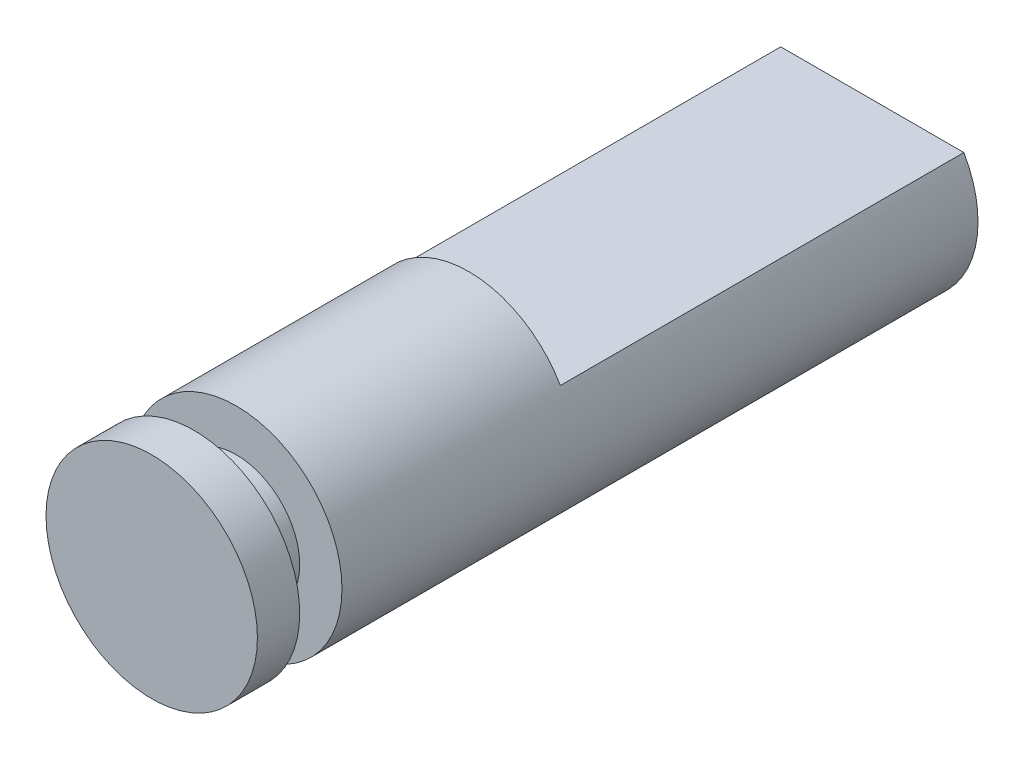
SolidWorks part; units mm, degrees
ref_plane "Front Plane" through (0, 0, 0) normal (0, 0, 1) x (1, 0, 0)
ref_plane "Top Plane" through (0, 0, 0) normal (0, 1, 0) x (1, 0, 0)
ref_plane "Right Plane" through (0, 0, 0) normal (1, 0, 0) x (0, 0, -1)
sketch "Sketch1" plane through (0, 0, 0) normal (0, 0, 1) x (1, 0, 0)
  line L1 (0, 2.5) -> (-4.3301, 2.5)
  line L2 (0, 2.5) -> (4.3301, 2.5)
  arc A0 (-4.3301, 2.5) -> (4.3301, 2.5) centre (0, 0) ccw
  dimension "D1" = 10
extrude "Boss-Extrude1" add sketch "Sketch1" along normal blind 19.0848
sketch "Sketch2" plane through (0, 0, 19.0848) normal (0, 0, 1) x (1, 0, 0)
  circle A0 centre (0, 0) radius 5
extrude "Boss-Extrude2" add sketch "Sketch2" along normal blind 15
ref_plane "Plane1" through (0, 0, 32.0848) normal (0, 0, 1) x (1, 0, 0)
sketch "Sketch3" plane through (0, 0, 32.0848) normal (0, 0, 1) x (1, 0, 0)
  circle A0 centre (0, 0) radius 3
  circle A1 centre (0, 0) radius 5
  circle A2 centre (0, 0) radius 5 construction
  dimension "D1" = 2
extrude "Cut-Extrude1" cut sketch "Sketch3" against normal blind 2
